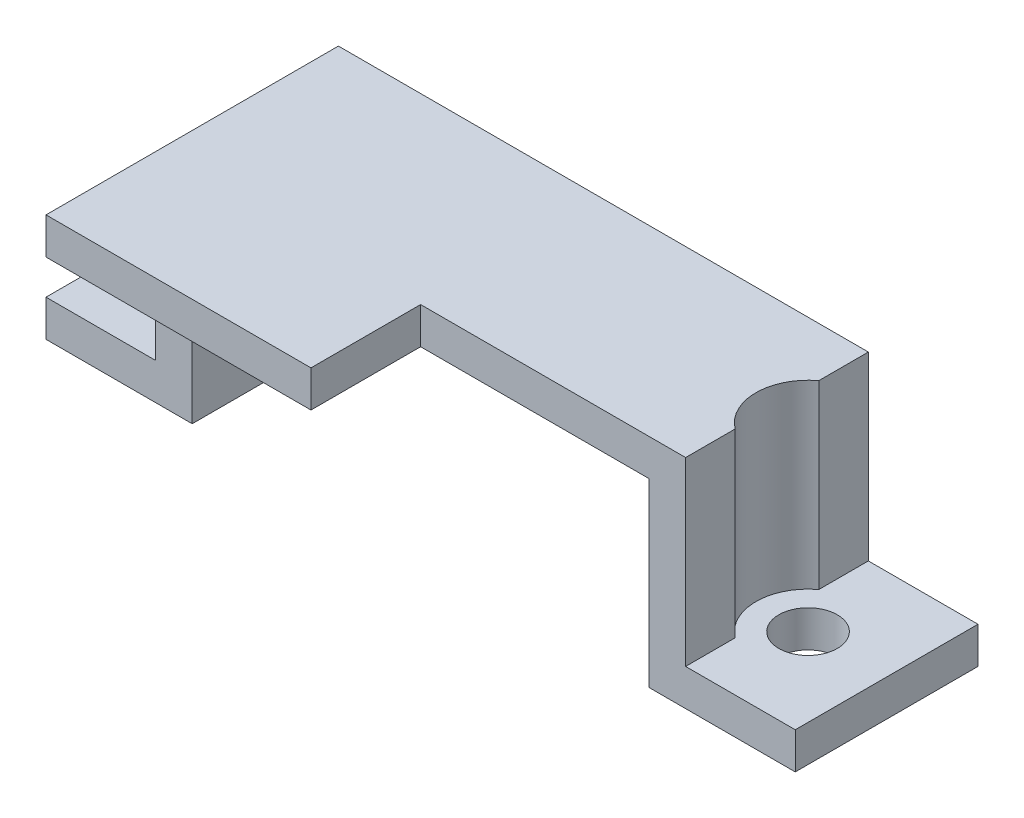
SolidWorks part; units mm, degrees
ref_plane "Ön Düzlem" through (0, 0, 0) normal (0, 0, 1) x (1, 0, 0)
ref_plane "Üst Düzlem" through (0, 0, 0) normal (0, 1, 0) x (1, 0, 0)
ref_plane "Sağ Düzlem" through (0, 0, 0) normal (1, 0, 0) x (0, 0, -1)
sketch "motor" plane through (0, 0, 0) normal (0, 0, 1) x (1, 0, 0)
  line L0 (-12, 10) -> (-12, 0) construction
  line L1 (-12, 10) -> (12, 10) construction
  line L2 (-12, 0) -> (12, 0) construction
  line L3 (12, 10) -> (12, 0) construction
  line L4 (0, 10) -> (0, 0) construction
  line L5 (12, 10) -> (0, 0) construction
  line L8 (0, 10) -> (12, 0) construction
  circle A0 centre (6, 5) radius 2
  point P2 (6, 5)
  dimension "D3" = 4
  dimension "D1" = 24
  dimension "D2" = 10
sketch "Çizim3" plane through (0, 0, 0) normal (0, 1, 0) x (1, 0, 0)
  line L0 (-20, 0) -> (-12, 0)
  line L1 (-12, 0) -> (12, 0) construction
  line L2 (-12, 0) -> (0, 0)
  line L3 (0, 0) -> (12, 0)
  line L4 (12, 0) -> (20, 0)
  line L5 (20, 0) -> (20, -10)
  line L6 (20, -10) -> (12, -10)
  line L7 (12, -10) -> (0, -10)
  line L8 (0, -10) -> (-1, -16)
  line L9 (-1, -16) -> (-11, -16)
  line L10 (-11, -16) -> (-12, -10)
  line L11 (-12, -10) -> (-20, -10)
  line L12 (-20, -10) -> (-20, 0)
  dimension "D1" = 10
  dimension "D2" = 24
  dimension "D3" = 10
  dimension "D4" = 8
  dimension "D5" = 6
sketch "Çizim4" plane through (0, 0, 0) normal (0, 0, 1) x (1, 0, 0)
  line L12 (-20, 2.1) -> (-14, 2.1)
  line L13 (-14, 2.1) -> (-14, 12)
  line L14 (-14, 12) -> (15, 12)
  line L15 (15, 12) -> (15, 2.1)
  line L16 (15, 2.1) -> (21, 2.1)
  line L17 (-12, 10) -> (-12, 0) construction
  line L19 (-12, 0) -> (12, 0) construction
  line L20 (-12, 10) -> (12, 10) construction
  dimension "D1" = 2
  dimension "D2" = 29
  dimension "D3" = 2.1
  dimension "D4" = 6
  dimension "D5" = 2
extrude "mount" add sketch "Çizim4" along normal blind 10 thin
sketch "Çizim5" plane through (0, 0, 10) normal (0, 0, 1) x (1, 0, 0)
  line L0 (-14, 12) -> (0.5, 12)
  line L1 (-14, 12) -> (15, 12) construction
extrude "motor üstü" add sketch "Çizim5" along normal blind 6 thin
sketch "Çizim6" plane through (0, 2.1, 0) normal (0, 1, 0) x (1, 0, 0)
  line L0 (0.5, 0) -> (0.5, -10) construction
  line L1 (-14, 0) -> (15, 0) construction
  line L2 (-17, -5) -> (-17, 0) construction
  line L3 (-20, 0) -> (-14, 0) construction
  line L5 (-20, -10) -> (-20, 0) construction
  line L6 (-20, -5) -> (-17, -5) construction
  circle A0 centre (-17, -5) radius 1.6
  circle A2 centre (16.7, -5) radius 1.6
  dimension "D2" = 3.2
extrude "cıvata delikleri" cut sketch "Çizim6" along normal blind 6 from surface at -2 contours A0 | A2 starting at face at (-16, 0.1, 5)
sketch "Çizim7" plane through (0, 2.1, 0) normal (0, 1, 0) x (1, 0, 0)
  circle A0 centre (16.7, -5) radius 2.85
  dimension "D1" = 5.7
extrude "Kes-Ekstrüzyon1" cut sketch "Çizim7" along normal up to surface (9.9 mm away) contours A0 up to face at (0.5, 12, 8.6667)
equation "\"D2@Çizim4\"=\"D1@Çizim4\"*2+25"
equation "\"D5@Çizim4\"=\"D1@Çizim4\""
